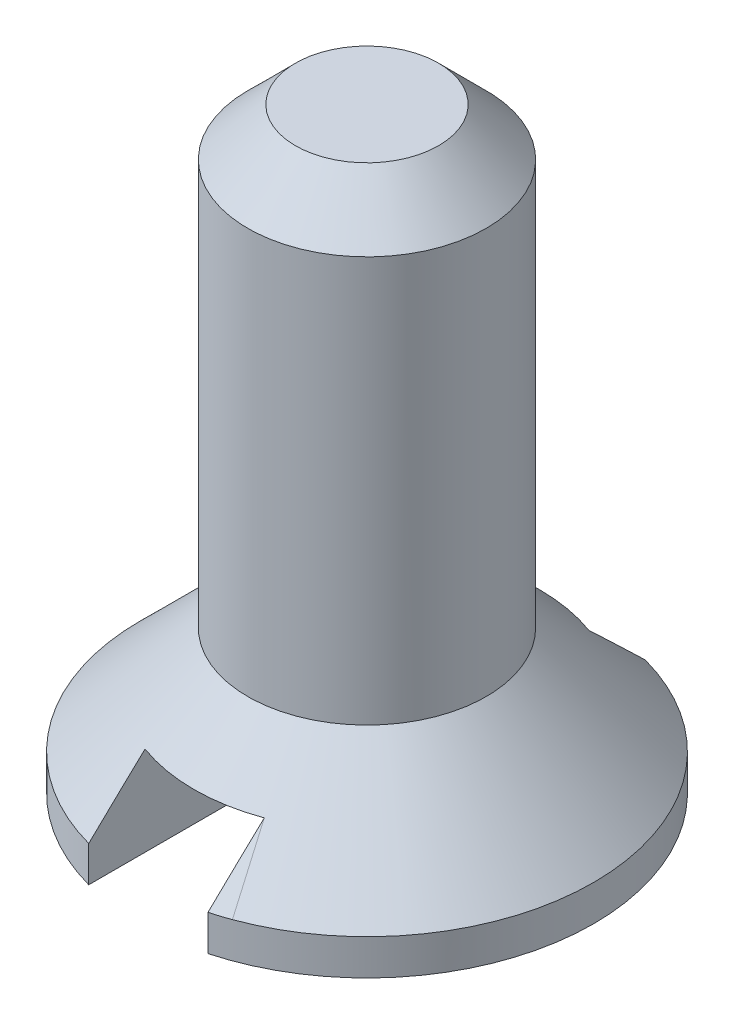
SolidWorks part; units mm, degrees
ref_plane "Спереди" through (0, 0, 0) normal (0, 0, 1) x (1, 0, 0)
ref_plane "Сверху" through (0, 0, 0) normal (0, 1, 0) x (1, 0, 0)
ref_plane "Справа" through (0, 0, 0) normal (1, 0, 0) x (0, 0, -1)
sketch "Эскиз1" plane through (0, 0, 0) normal (0, 0, 1) x (1, 0, 0)
  line L0 (0, 0) -> (-1.9, 0)
  line L1 (-1.9, 0) -> (-1.9, 0.3)
  line L2 (-1.9, 0.3) -> (-1, 1.2)
  line L3 (-1, 1.2) -> (-1, 5)
  line L4 (-1, 5) -> (0, 5)
  line L5 (0, 5) -> (0, 0)
  line L6 (-1, 1.2) -> (0, 1.2) construction
  dimension "D1" = 5
  dimension "D2" = 1.9
  dimension "D3" = 1
  dimension "D4" = 45
  dimension "D5" = 1.2
revolve "Повернуть1" add sketch "Эскиз1" angle 360 about L5
sketch "Эскиз2" plane through (0, 0, 0) normal (0, 0, 1) x (1, 0, 0)
  line L0 (-1.9, 0) -> (1.9, 0) construction
  line L1 (-0.5, 0) -> (0.5, 0)
  line L2 (-0.5, 0) -> (-0.5, 0.75)
  line L3 (-0.5, 0.75) -> (0.5, 0.75)
  line L4 (0.5, 0) -> (0.5, 0.75)
  dimension "D1" = 0.75
  dimension "D2" = 1
extrude "Вырез-Вытянуть1" cut sketch "Эскиз2" against normal mid plane 20
chamfer "Фаска1" distance 0.4 angle 45 1 edges at (-1, 5, 0)
